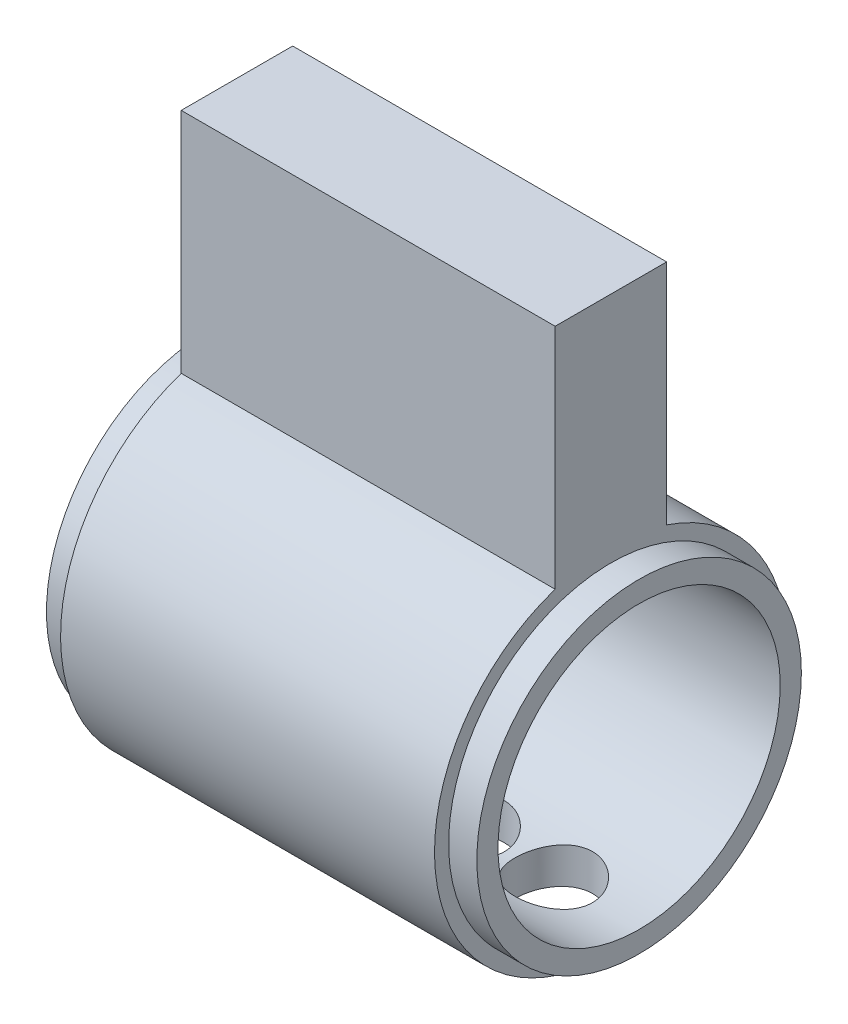
SolidWorks part; units mm, degrees
material "Zinc AC41A Alloy, As Cast"
ref_plane "Front" through (0, 0, 0) normal (0, 0, 1) x (1, 0, 0)
ref_plane "Top" through (0, 0, 0) normal (0, 1, 0) x (1, 0, 0)
ref_plane "Right" through (0, 0, 0) normal (1, 0, 0) x (0, 0, -1)
sketch "Sketch1" plane through (0, 0, 0) normal (1, 0, 0) x (0, 0, -1)
  circle A0 centre (0, 0) radius 6.35
  circle A1 centre (0, 0) radius 5.08
  dimension "D1" = 12.7
  dimension "D2" = 10.16
extrude "Boss-Extrude1" add sketch "Sketch1" along normal blind 15.494
ref_plane "Plane1" through (1.016, 0, 0) normal (1, 0, 0) x (0, 0, -1)
sketch "Sketch2" plane through (1.016, 0, 0) normal (1, 0, 0) x (0, 0, -1)
  line L0 (-2.0066, 6.0246) -> (-2.0066, 14.224)
  line L1 (-2.0066, 14.224) -> (2.0066, 14.224)
  line L2 (2.0066, 14.224) -> (2.0066, 6.0246)
  circle A0 centre (0, 0) radius 6.35 construction
  arc A1 (2.0066, 6.0246) -> (-2.0066, 6.0246) centre (0, 0) ccw
  circle A2 centre (0, 0) radius 5.08 construction
  point P7 (0, 14.224)
  point P9 (0, 6.35)
  point P14 (0, 5.08)
  dimension "D1" = 7.874
  dimension "D2" = 4.0132
extrude "Boss-Extrude2" add sketch "Sketch2" along normal offset from surface (13.462 mm away) 1.016 up to face at (15.494, 0, -6.35)
sketch "Sketch3" plane through (0, 0, 0) normal (0, 0, 1) x (1, 0, 0)
  line L5 (15.494, 6.35) -> (14.478, 6.35)
  line L6 (14.478, 6.35) -> (14.478, 5.842)
  line L7 (14.478, 14.224) -> (14.478, 6.0246) construction
  line L8 (14.478, 5.842) -> (15.494, 5.842)
  line L9 (15.494, -6.35) -> (15.494, 6.35) construction
  line L10 (15.494, 5.842) -> (15.494, 6.35)
  line L14 (0, 6.35) -> (1.016, 6.35)
  line L15 (1.016, -50) -> (1.016, 50) construction
  line L16 (1.016, 6.35) -> (1.016, 5.842)
  line L17 (1.016, 5.842) -> (0, 5.842)
  line L18 (0, 6.35) -> (0, -6.35) construction
  line L19 (0, 5.842) -> (0, 6.35)
  dimension "D1" = 0.508
revolve "Cut-Revolve1" cut sketch "Sketch3" angle 360 about axis through (15.494, 0, 0) along (-1, 0, 0)
sketch "Sketch5" plane through (0, 0, 0) normal (-1, 0, 0) x (0, 0, 1)
  line L6 (4.7093, 0.635) -> (4.7093, -1.905)
  line L14 (4.7093, 0.635) -> (5.0402, 0.635)
  arc A1 (5.0402, 0.635) -> (4.7093, -1.905) centre (0, 0) cw
  circle A2 centre (0, 0) radius 5.08 construction
  point P3 (5.0903, 0)
  dimension "D3" = 0.635
  dimension "D1" = 2.54
  dimension "D2" = 0.381
extrude "Boss-Extrude3" add sketch "Sketch5" against normal blind 1.27
ref_plane "Plane2" through (0, -6.35, 0) normal (0, 1, 0) x (1, 0, 0)
sketch "Sketch7" plane through (0, -6.35, 0) normal (0, 1, 0) x (1, 0, 0)
  line L0 (14.478, 0) -> (1.016, 0) construction
  line L1 (12.4206, 0) -> (9.2456, 0) construction
  line L2 (9.2456, 0) -> (6.0706, 0) construction
  line L3 (6.0706, 0) -> (2.8956, 0) construction
  line L10 (15.494, -5.842) -> (15.494, 5.842) construction
  circle A3 centre (12.4206, 0) radius 1.397
  circle A4 centre (2.8956, 0) radius 1.397
  circle A5 centre (6.0706, 0) radius 1.397
  circle A6 centre (9.2456, 0) radius 1.397
  dimension "D1" = 3.175
  dimension "D2" = 2.794
  dimension "D3" = 3.0734
extrude "Cut-Extrude1" cut sketch "Sketch7" along normal blind 20.32
sketch "Sketch11" plane through (0, 0, 0) normal (0, 1, 0) x (1, 0, 0)
  line L1 (1.27, -4.7093) -> (1.27, -5.0402)
  line L4 (1.27, -5.0402) -> (0, -4.7093)
  line L5 (1.27, -4.7093) -> (0, -4.7093)
extrude "Cut-Extrude4" cut sketch "Sketch11" against normal up to surface and the other way up to surface (0.635 mm away) up to face at (2.6316, -4.8913, 1.3718)
